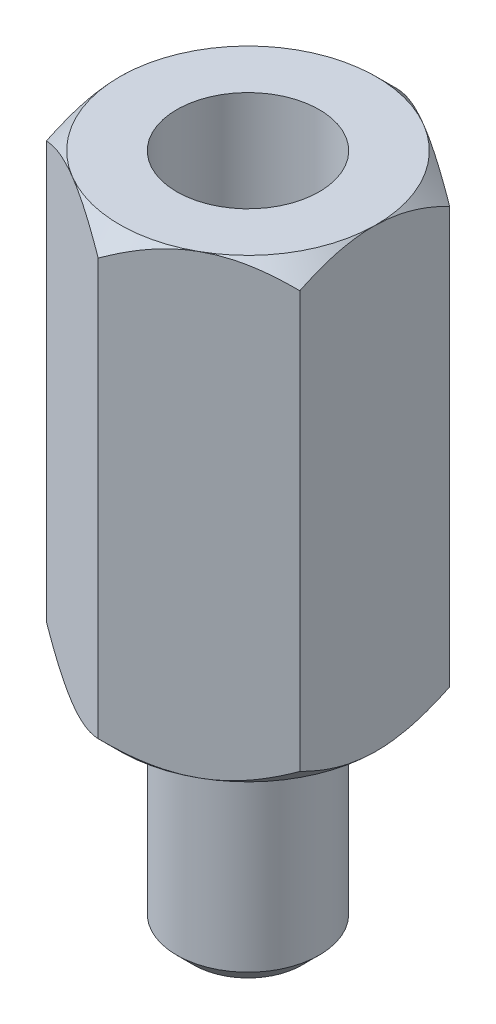
SolidWorks part; units mm, degrees
ref_plane "Front Plane" through (0, 0, 0) normal (0, 0, 1) x (1, 0, 0)
ref_plane "Top Plane" through (0, 0, 0) normal (0, 1, 0) x (1, 0, 0)
ref_plane "Right Plane" through (0, 0, 0) normal (1, 0, 0) x (0, 0, -1)
sketch "Sketch1" plane through (0, 0, 0) normal (0, 1, 0) x (1, 0, 0)
  circle A0 centre (0, 0) radius 1.25
  dimension "D1" = 2.5
extrude "Boss-Extrude1" add sketch "Sketch1" along normal blind 3.9
sketch "Sketch2" plane through (0, 3.9, 0) normal (0, 1, 0) x (1, 0, 0)
  line L1 (2.2348, -1.325) -> (2.2649, 1.2729)
  line L2 (2.2649, 1.2729) -> (0.0301, 2.5979)
  line L3 (0.0301, 2.5979) -> (-2.2348, 1.325)
  line L4 (-2.2348, 1.325) -> (-2.2649, -1.2729)
  line L5 (-2.2649, -1.2729) -> (-0.0301, -2.5979)
  line L6 (-0.0301, -2.5979) -> (2.2348, -1.325)
  circle A0 centre (0, 0) radius 2.25 construction
  dimension "D1" = 4.5
extrude "Boss-Extrude2" add sketch "Sketch2" along normal blind 8
sketch "Sketch3" plane through (0, 11.9, 0) normal (0, 1, 0) x (1, 0, 0)
  circle A0 centre (0, 0) radius 1.25
  dimension "D1" = 2.5
extrude "Cut-Extrude1" cut sketch "Sketch3" against normal blind 4.8
sketch "Sketch5" plane through (0, 11.9, 0) normal (0, 1, 0) x (1, 0, 0)
  circle A0 centre (0, 0) radius 2.25
extrude "Cut-Extrude2" cut sketch "Sketch5" against normal through all draft 45 flip side to cut
sketch "Sketch6" plane through (0, 3.9, 0) normal (0, -1, 0) x (1, 0, 0)
  circle A0 centre (0, 0) radius 2.25
extrude "Cut-Extrude3" cut sketch "Sketch6" against normal through all draft 45 flip side to cut
chamfer "Chamfer1" distance 0.3 angle 45 1 edges at (0, 0, 1.25)
